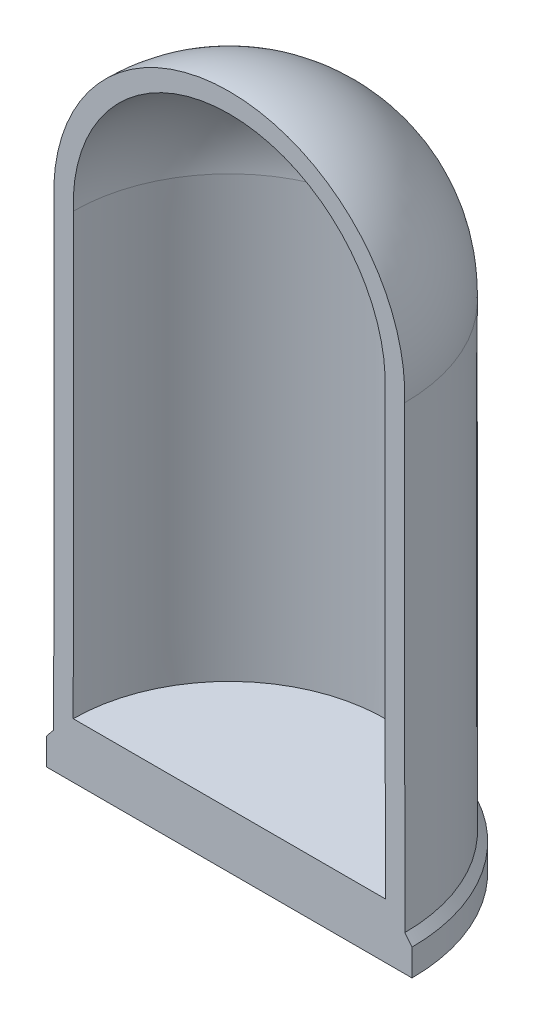
SolidWorks part; units mm, degrees
ref_plane "Front Plane" through (0, 0, 0) normal (0, 0, 1) x (1, 0, 0)
ref_plane "Top Plane" through (0, 0, 0) normal (0, 1, 0) x (1, 0, 0)
ref_plane "Right Plane" through (0, 0, 0) normal (1, 0, 0) x (0, 0, -1)
sketch "Sketch1" plane through (0, 0, 0) normal (0, 0, 1) x (1, 0, 0)
  line L0 (0, 0) -> (175, 0)
  line L1 (0, -21.875) -> (196.8809, -21.875)
  line L2 (175, 0) -> (174.8623, 506.9421)
  line L3 (174.8641, 500) -> (175, 500)
  line L4 (196.8809, -21.875) -> (196.7373, 506.9481)
  line L5 (0, 696.875) -> (0, 675)
  line L6 (0, 0) -> (0, -21.875)
  line L7 (196.8809, -21.875) -> (205, -31.875)
  line L8 (205, -31.875) -> (205, -61.875)
  line L9 (205, -61.875) -> (0, -61.875)
  line L10 (0, -61.875) -> (0, -21.875)
  line L11 (0, 914.7733) -> (0, -531.4435) construction
  line L12 (0, -23.6036) -> (0, -61.875)
  arc A0 (174.866, 493.1529) -> (0, 675) centre (0, 500) ccw
  arc A1 (196.7242, 492.297) -> (0, 696.875) centre (0, 500) ccw
  dimension "D1" = 500
  dimension "D2" = 350
  dimension "D4" = 30
  dimension "D5" = 10
  dimension "D6" = 205
  dimension "D3" = 21.875
revolve "Revolve6" add sketch "Sketch1" angle 180 about L11
